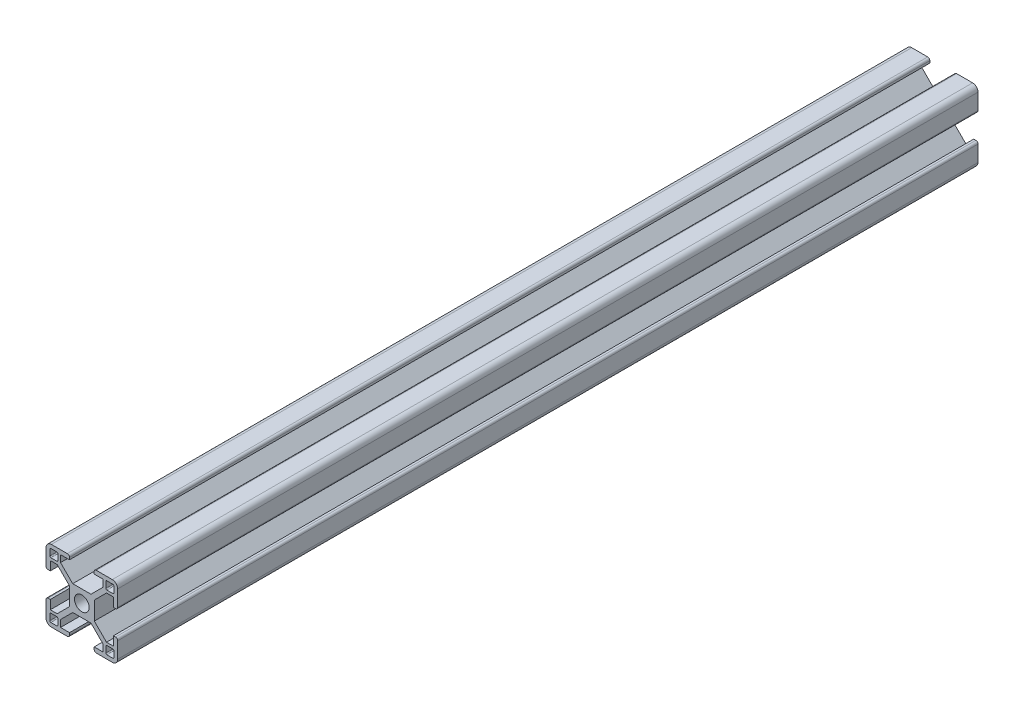
SolidWorks part; units mm, degrees
ref_plane "Alzado" through (0, 0, 0) normal (0, 0, 1) x (1, 0, 0)
ref_plane "Planta" through (0, 0, 0) normal (0, 1, 0) x (1, 0, 0)
ref_plane "Vista lateral" through (0, 0, 0) normal (1, 0, 0) x (0, 0, -1)
sketch "Croquis1" plane through (0, 0, 0) normal (0, 0, 1) x (1, 0, 0)
  line L0 (-5.8, 0) -> (5.8, 0) construction
  line L1 (5.8, -4.24) -> (5.8, 4.24)
  line L2 (5.8, 4.24) -> (11.47, 9.91)
  line L3 (11.47, 9.91) -> (14.66, 9.91)
  line L4 (14.66, 9.91) -> (14.66, 5.73)
  line L5 (14.66, 5.73) -> (15.66, 5.73)
  line L6 (16.66, 6.73) -> (16.66, 14.16)
  line L7 (0, 0) -> (16.66, 16.66) construction
  line L8 (5.73, 14.66) -> (5.73, 15.66)
  line L9 (6.73, 16.66) -> (14.16, 16.66)
  line L10 (9.91, 14.66) -> (5.73, 14.66)
  line L11 (9.91, 11.47) -> (9.91, 14.66)
  line L12 (4.24, 5.8) -> (9.91, 11.47)
  line L13 (-4.24, 5.8) -> (4.24, 5.8)
  line L14 (0, 5.8) -> (0, -5.8) construction
  line L15 (11.6515, 14.9015) -> (14.4015, 14.9015)
  line L16 (11.1515, 14.4015) -> (11.1515, 11.6515)
  line L17 (11.6515, 11.1515) -> (14.4015, 11.1515)
  line L18 (14.9015, 14.4015) -> (14.9015, 11.6515)
  line L19 (11.1515, 14.9015) -> (14.9015, 11.1515) construction
  line L20 (11.1515, 11.1515) -> (14.9015, 14.9015) construction
  line L21 (-11.1515, 11.1515) -> (-14.9015, 14.9015) construction
  line L22 (-11.1515, 14.9015) -> (-14.9015, 11.1515) construction
  line L23 (0, 0) -> (-16.66, 16.66) construction
  line L24 (-14.9015, 14.4015) -> (-14.9015, 11.6515)
  line L25 (-11.6515, 11.1515) -> (-14.4015, 11.1515)
  line L26 (-11.1515, 14.4015) -> (-11.1515, 11.6515)
  line L27 (-11.6515, 14.9015) -> (-14.4015, 14.9015)
  line L28 (-4.24, 5.8) -> (-9.91, 11.47)
  line L29 (-9.91, 11.47) -> (-9.91, 14.66)
  line L30 (-9.91, 14.66) -> (-5.73, 14.66)
  line L31 (-6.73, 16.66) -> (-14.16, 16.66)
  line L32 (-5.73, 14.66) -> (-5.73, 15.66)
  line L33 (-16.66, 6.73) -> (-16.66, 14.16)
  line L34 (-14.66, 5.73) -> (-15.66, 5.73)
  line L35 (-14.66, 9.91) -> (-14.66, 5.73)
  line L36 (-11.47, 9.91) -> (-14.66, 9.91)
  line L37 (-5.8, 4.24) -> (-11.47, 9.91)
  line L38 (-5.8, -4.24) -> (-5.8, 4.24)
  line L39 (0, 0) -> (-16.66, -16.66) construction
  line L40 (-11.1515, -14.9015) -> (-14.9015, -11.1515) construction
  line L41 (-11.1515, -11.1515) -> (-14.9015, -14.9015) construction
  line L42 (11.1515, -11.1515) -> (14.9015, -14.9015) construction
  line L43 (11.1515, -14.9015) -> (14.9015, -11.1515) construction
  line L44 (0, 0) -> (16.66, -16.66) construction
  line L45 (-5.8, -4.24) -> (-11.47, -9.91)
  line L46 (-11.47, -9.91) -> (-14.66, -9.91)
  line L47 (-14.66, -9.91) -> (-14.66, -5.73)
  line L48 (-14.66, -5.73) -> (-15.66, -5.73)
  line L49 (-16.66, -6.73) -> (-16.66, -14.16)
  line L50 (-5.73, -14.66) -> (-5.73, -15.66)
  line L51 (-6.73, -16.66) -> (-14.16, -16.66)
  line L52 (-9.91, -14.66) -> (-5.73, -14.66)
  line L53 (-9.91, -11.47) -> (-9.91, -14.66)
  line L54 (-4.24, -5.8) -> (-9.91, -11.47)
  line L55 (-11.6515, -14.9015) -> (-14.4015, -14.9015)
  line L56 (-11.1515, -14.4015) -> (-11.1515, -11.6515)
  line L57 (-11.6515, -11.1515) -> (-14.4015, -11.1515)
  line L58 (-14.9015, -14.4015) -> (-14.9015, -11.6515)
  line L59 (14.9015, -14.4015) -> (14.9015, -11.6515)
  line L60 (11.6515, -11.1515) -> (14.4015, -11.1515)
  line L61 (11.1515, -14.4015) -> (11.1515, -11.6515)
  line L62 (11.6515, -14.9015) -> (14.4015, -14.9015)
  line L63 (-4.24, -5.8) -> (4.24, -5.8)
  line L64 (4.24, -5.8) -> (9.91, -11.47)
  line L65 (9.91, -11.47) -> (9.91, -14.66)
  line L66 (9.91, -14.66) -> (5.73, -14.66)
  line L67 (6.73, -16.66) -> (14.16, -16.66)
  line L68 (5.73, -14.66) -> (5.73, -15.66)
  line L69 (16.66, -6.73) -> (16.66, -14.16)
  line L70 (14.66, -5.73) -> (15.66, -5.73)
  line L71 (14.66, -9.91) -> (14.66, -5.73)
  line L72 (11.47, -9.91) -> (14.66, -9.91)
  line L73 (5.8, -4.24) -> (11.47, -9.91)
  arc A0 (15.66, 5.73) -> (16.66, 6.73) centre (15.66, 6.73) ccw
  arc A1 (16.66, 14.16) -> (14.16, 16.66) centre (14.16, 14.16) ccw
  arc A2 (5.73, 15.66) -> (6.73, 16.66) centre (6.73, 15.66) cw
  arc A3 (11.1515, 11.6515) -> (11.6515, 11.1515) centre (11.6515, 11.6515) ccw
  arc A4 (14.4015, 11.1515) -> (14.9015, 11.6515) centre (14.4015, 11.6515) ccw
  arc A5 (14.4015, 14.9015) -> (14.9015, 14.4015) centre (14.4015, 14.4015) cw
  arc A6 (11.6515, 14.9015) -> (11.1515, 14.4015) centre (11.6515, 14.4015) ccw
  arc A7 (-11.6515, 14.9015) -> (-11.1515, 14.4015) centre (-11.6515, 14.4015) cw
  arc A8 (-14.4015, 14.9015) -> (-14.9015, 14.4015) centre (-14.4015, 14.4015) ccw
  arc A9 (-14.4015, 11.1515) -> (-14.9015, 11.6515) centre (-14.4015, 11.6515) cw
  arc A10 (-11.1515, 11.6515) -> (-11.6515, 11.1515) centre (-11.6515, 11.6515) cw
  arc A11 (-5.73, 15.66) -> (-6.73, 16.66) centre (-6.73, 15.66) ccw
  arc A12 (-16.66, 14.16) -> (-14.16, 16.66) centre (-14.16, 14.16) cw
  arc A13 (-15.66, 5.73) -> (-16.66, 6.73) centre (-15.66, 6.73) cw
  arc A14 (-15.66, -5.73) -> (-16.66, -6.73) centre (-15.66, -6.73) ccw
  arc A15 (-16.66, -14.16) -> (-14.16, -16.66) centre (-14.16, -14.16) ccw
  arc A16 (-5.73, -15.66) -> (-6.73, -16.66) centre (-6.73, -15.66) cw
  arc A17 (-11.1515, -11.6515) -> (-11.6515, -11.1515) centre (-11.6515, -11.6515) ccw
  arc A18 (-14.4015, -11.1515) -> (-14.9015, -11.6515) centre (-14.4015, -11.6515) ccw
  arc A19 (-14.4015, -14.9015) -> (-14.9015, -14.4015) centre (-14.4015, -14.4015) cw
  arc A20 (-11.6515, -14.9015) -> (-11.1515, -14.4015) centre (-11.6515, -14.4015) ccw
  arc A21 (11.6515, -14.9015) -> (11.1515, -14.4015) centre (11.6515, -14.4015) cw
  arc A22 (14.4015, -14.9015) -> (14.9015, -14.4015) centre (14.4015, -14.4015) ccw
  arc A23 (14.4015, -11.1515) -> (14.9015, -11.6515) centre (14.4015, -11.6515) cw
  arc A24 (11.1515, -11.6515) -> (11.6515, -11.1515) centre (11.6515, -11.6515) cw
  arc A25 (5.73, -15.66) -> (6.73, -16.66) centre (6.73, -15.66) ccw
  arc A26 (16.66, -14.16) -> (14.16, -16.66) centre (14.16, -14.16) cw
  arc A27 (15.66, -5.73) -> (16.66, -6.73) centre (15.66, -6.73) cw
  circle A28 centre (0, 0) radius 3.4
  point P24 (13.0265, 13.0265)
  point P76 (-13.0265, 13.0265)
  point P77 (-5.73, 16.66)
  point P78 (-16.66, 5.73)
  point P148 (-16.66, -5.73)
  point P149 (-5.73, -16.66)
  point P150 (-13.0265, -13.0265)
  point P151 (13.0265, -13.0265)
  point P152 (5.73, -16.66)
  point P153 (16.66, -5.73)
  dimension "D9" = 1
  dimension "D10" = 2.5
  dimension "D11" = 1
  dimension "D14" = 0.5
  dimension "D15" = 6.8
  dimension "D2" = 4.24
  dimension "D3" = 135
  dimension "D4" = 5.67
  dimension "D5" = 3.19
  dimension "D6" = 4.18
  dimension "D12" = 3.75
  dimension "D13" = 3.75
extrude "Saliente-Extruir1" add sketch "Croquis1" along normal blind 400
